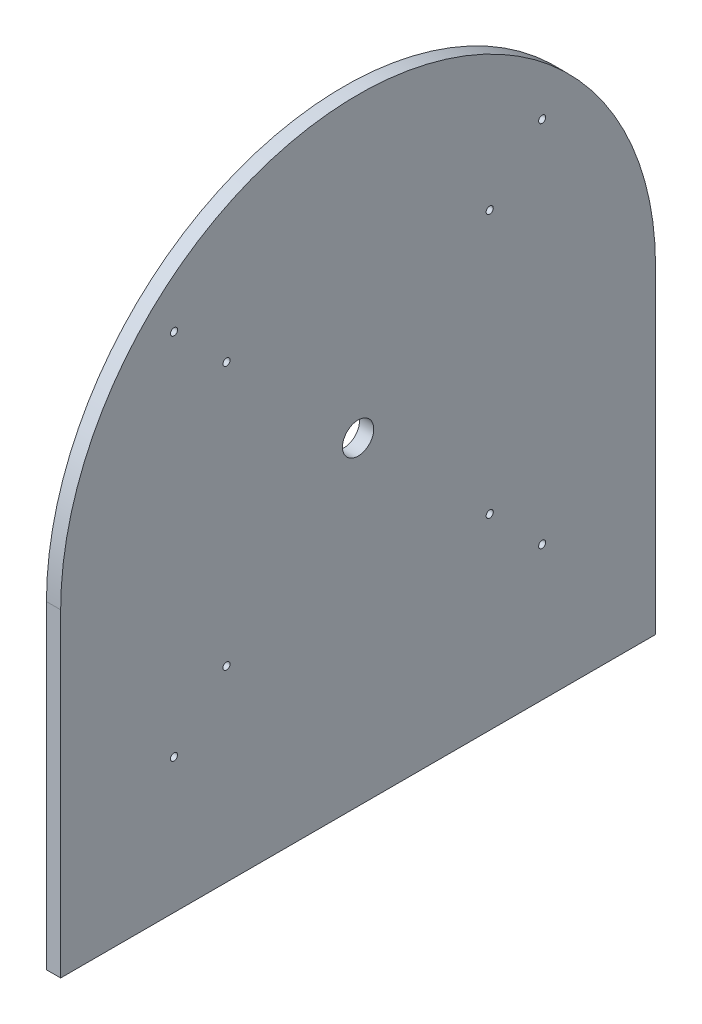
SolidWorks part; units mm, degrees
ref_plane "Front Plane" through (0, 0, 0) normal (0, 0, 1) x (1, 0, 0)
ref_plane "Top Plane" through (0, 0, 0) normal (0, 1, 0) x (1, 0, 0)
ref_plane "Right Plane" through (0, 0, 0) normal (1, 0, 0) x (0, 0, -1)
sketch "Sketch1" plane through (0, 0, 0) normal (1, 0, 0) x (0, 0, -1)
  line L1 (209.31, -224.4) -> (-209.31, -224.4)
  line L2 (209.31, -224.4) -> (209.31, 0)
  line L3 (209.31, 0) -> (-209.31, 0)
  line L4 (-209.31, -224.4) -> (-209.31, 0)
  line L5 (209.31, -224.4) -> (-209.31, 0) construction
  line L6 (209.31, 0) -> (-209.31, -224.4) construction
  circle A0 centre (0, 0) radius 209.31
  point P2 (0, -112.2)
  dimension "D1" = 418.62
  dimension "D2" = 224.4
extrude "Boss-Extrude1" add sketch "Sketch1" along normal blind 10 contours L3 A0 | L3 A0 | A0 L4 L1 L2
sketch "Sketch2" plane through (10, 0, 0) normal (1, 0, 0) x (0, 0, -1)
  line L0 (116.7928, 116.7928) -> (0, 0) construction
  line L1 (0, 0) -> (0, 165.17) construction
  line L2 (92.6098, 92.6098) -> (129.5349, 129.5349)
  circle A0 centre (0, 0) radius 165.17
  circle A3 centre (0, 0) radius 157.08
  circle A4 centre (129.5349, 129.5349) radius 2.5
  circle A5 centre (92.6098, 92.6098) radius 2.5
  circle A6 centre (92.6098, -92.6098) radius 2.5
  circle A7 centre (129.5349, -129.5349) radius 2.5
  circle A8 centre (-92.6098, -92.6098) radius 2.5
  circle A9 centre (-129.5349, -129.5349) radius 2.5
  circle A10 centre (-92.6098, 92.6098) radius 2.5
  circle A11 centre (-129.5349, 129.5349) radius 2.5
  point P9 (111.0723, 111.0723)
  point P10 (153.2003, 34.6957)
  dimension "D1" = 330.34
  dimension "D3" = 52.22
  dimension "D4" = 8.09
  dimension "D5" = 5
  dimension "D6" = 5
  dimension "D2" = 45
  dimension "D7" = 4
extrude "Cut-Extrude1" cut sketch "Sketch2" against normal blind 10
sketch "Sketch3" plane through (10, 0, 0) normal (1, 0, 0) x (0, 0, -1)
  circle A0 centre (0, 0) radius 11
  dimension "D1" = 22
extrude "Cut-Extrude2" cut sketch "Sketch3" against normal blind 10
